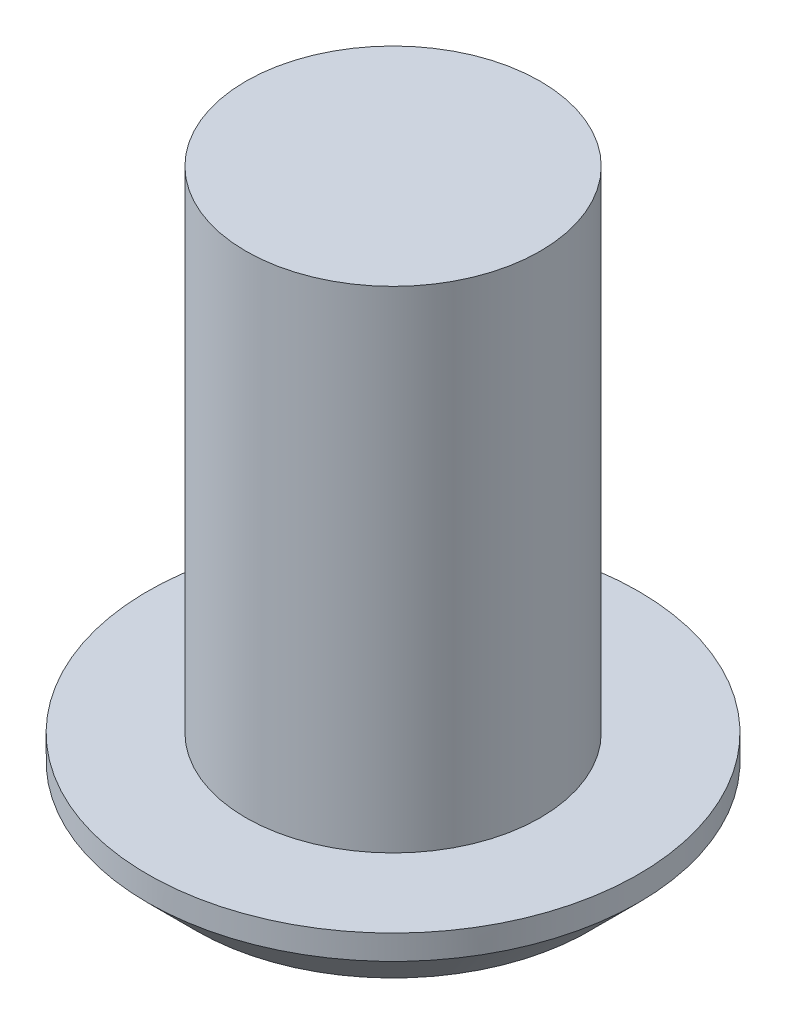
SolidWorks part; units mm, degrees
material "6061-T6 (SS)"
ref_plane "Front Plane" through (0, 0, 0) normal (1, 0, 0) x (0, 1, 0)
ref_plane "Top Plane" through (0, 0, 0) normal (0, 0, 1) x (0, 1, 0)
ref_plane "Right Plane" through (0, 0, 0) normal (0, 1, 0) x (-1, 0, 0)
sketch "Sketch1" plane through (0, 0, 0) normal (1, 0, 0) x (0, 1, 0)
  line L0 (-2.3014, 0) -> (3.7052, 0) construction
  line L1 (10, 0) -> (10, 3)
  line L2 (10, 3) -> (0, 3)
  line L3 (0, 3) -> (0, 0)
  line L4 (0, 0) -> (0, 5)
  line L5 (0, 5) -> (-1.5, 5)
  line L6 (-1.5, 5) -> (-1.5, 0)
  line L7 (-1.5, 0) -> (10, 0)
  dimension "D1" = 1.5
  dimension "D2" = 10
  dimension "D3" = 6
  dimension "D4" = 10
revolve "Revolve1" add sketch "Sketch1" angle 360 about L0
chamfer "Chamfer1" distance 1 angle 45 1 edges at (0, -1.5, -5)
